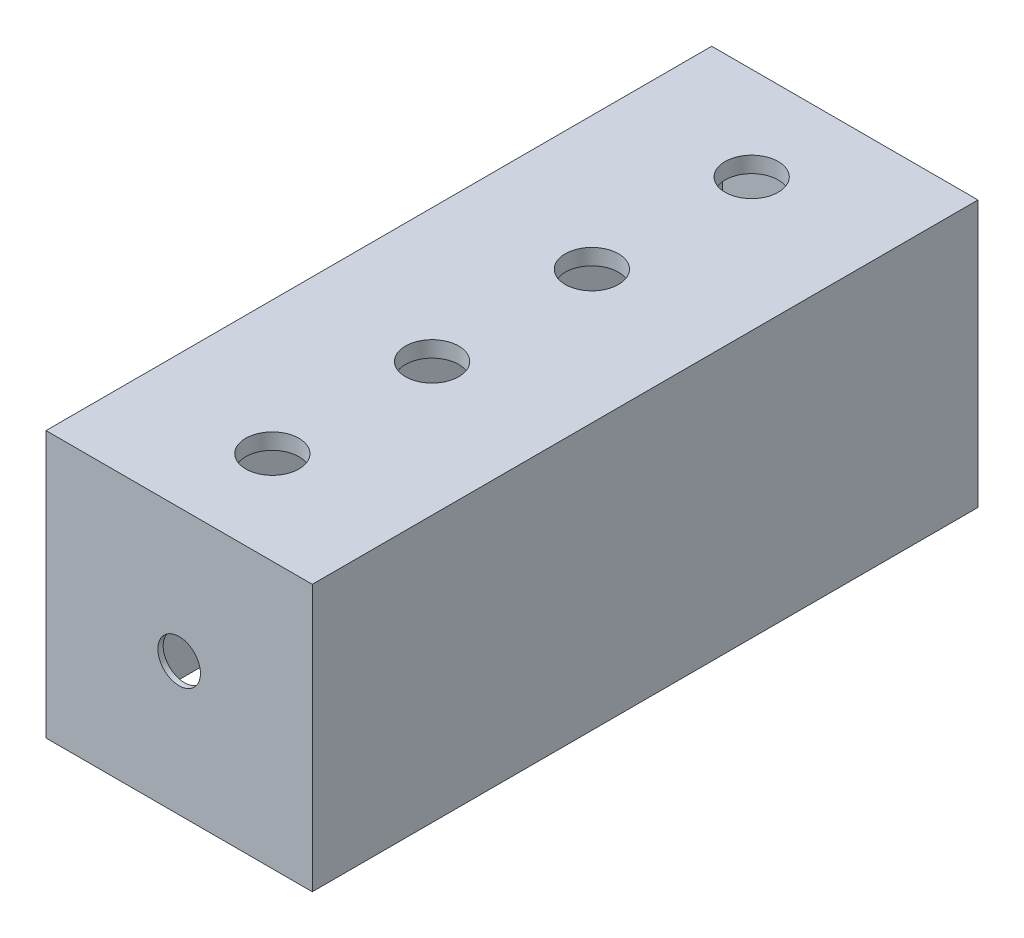
SolidWorks part; units mm, degrees
ref_plane "Front Plane" through (0, 0, 0) normal (0, 0, 1) x (1, 0, 0)
ref_plane "Top Plane" through (0, 0, 0) normal (0, 1, 0) x (1, 0, 0)
ref_plane "Right Plane" through (0, 0, 0) normal (1, 0, 0) x (0, 0, -1)
sketch "Sketch1" plane through (0, 0, 0) normal (0, 0, 1) x (1, 0, 0)
  line L1 (0, 0) -> (-50, 0)
  line L2 (0, 0) -> (0, 50)
  line L3 (0, 50) -> (-50, 50)
  line L4 (-50, 0) -> (-50, 50)
  dimension "D1" = 50
extrude "Boss-Extrude1" add sketch "Sketch1" along normal blind 125
sketch "Sketch2" plane through (0, 50, 0) normal (0, 1, 0) x (1, 0, 0)
  line L0 (0, -125) -> (-50, -125) construction
  circle A0 centre (-25, -17.5) radius 5
  circle A1 centre (-25, -47.5) radius 5
  circle A2 centre (-25, -77.5) radius 5
  circle A3 centre (-25, -107.5) radius 5
  point P8 (0, 0)
  dimension "D4" = 10
  dimension "D1" = 30
  dimension "D2" = 30
  dimension "D3" = 30
  dimension "D5" = 17.5
extrude "Cut-Extrude1" cut sketch "Sketch2" against normal blind 145
sketch "Sketch3" plane through (0, 0, 0) normal (0, 0, -1) x (-1, 0, 0)
  circle A0 centre (25, 25) radius 4
extrude "Cut-Extrude2" cut sketch "Sketch3" against normal blind 145
sketch "Sketch4" plane through (0, 0, 0) normal (0, -1, 0) x (-1, 0, 0)
  line L0 (50, -125) -> (50, 0) construction
  line L1 (47, -124) -> (3, -124)
  line L2 (47, -124) -> (47, -1)
  line L3 (47, -1) -> (3, -1)
  line L4 (3, -124) -> (3, -1)
  line L5 (47, -75.699) -> (50, -75.699)
  line L6 (47, -75.699) -> (47, -75.54)
  line L7 (47, -75.54) -> (50, -75.54)
  line L8 (50, -75.699) -> (50, -75.54)
  line L9 (0, -125) -> (0, 0) construction
  line L10 (50, 0) -> (0, 0) construction
  line L11 (50, -125) -> (0, -125) construction
  circle M5 centre (25, -17.5) radius 5
  circle M6 centre (25, -47.5) radius 5
  circle M7 centre (25, -77.5) radius 5
  circle M8 centre (25, -107.5) radius 5
  dimension "D1" = 3
  dimension "D2" = 3
  dimension "D3" = 1
  dimension "D4" = 1
extrude "Cut-Extrude3" cut sketch "Sketch4" against normal blind 47 contours L4 L1 L2 L3 M6 M8 M7 M5
sketch "Sketch5" plane through (0, 0, 0) normal (0, -1, 0) x (-1, 0, 0)
  line L0 (50, -125) -> (0, -125) construction
  line L1 (50, 0) -> (0, 0) construction
  circle A0 centre (48.5156, -122) radius 1
  circle A1 centre (1.5948, -122) radius 1
  circle A2 centre (48.5156, -3) radius 1
  circle A3 centre (1.5948, -3) radius 1
  dimension "D1" = 2
  dimension "D2" = 3
  dimension "D3" = 3
  dimension "D4" = 3
  dimension "D5" = 3
extrude "Cut-Extrude4" cut sketch "Sketch5" against normal blind 5
